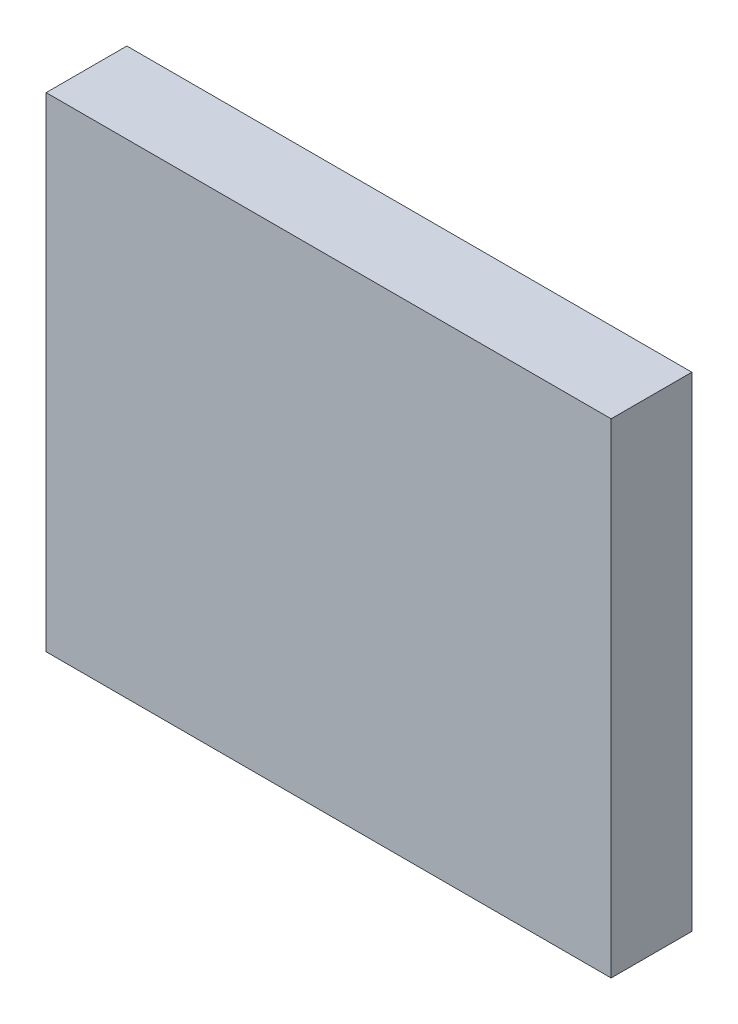
SolidWorks part; units mm, degrees
ref_plane "Face" through (0, 0, 0) normal (0, 0, 1) x (1, 0, 0)
ref_plane "Dessus" through (0, 0, 0) normal (0, 1, 0) x (1, 0, 0)
ref_plane "Droite" through (0, 0, 0) normal (1, 0, 0) x (0, 0, -1)
sketch "Esquisse1" plane through (0, 0, 0) normal (0, 0, 1) x (1, 0, 0)
  line L1 (-22.4631, 43.6808) -> (47.5369, 43.6808)
  line L2 (-22.4631, 43.6808) -> (-22.4631, -16.3192)
  line L3 (-22.4631, -16.3192) -> (47.5369, -16.3192)
  line L4 (47.5369, 43.6808) -> (47.5369, -16.3192)
  dimension "D1" = 70
  dimension "D2" = 60
extrude "Base-Extrusion" add sketch "Esquisse1" along normal blind 10
